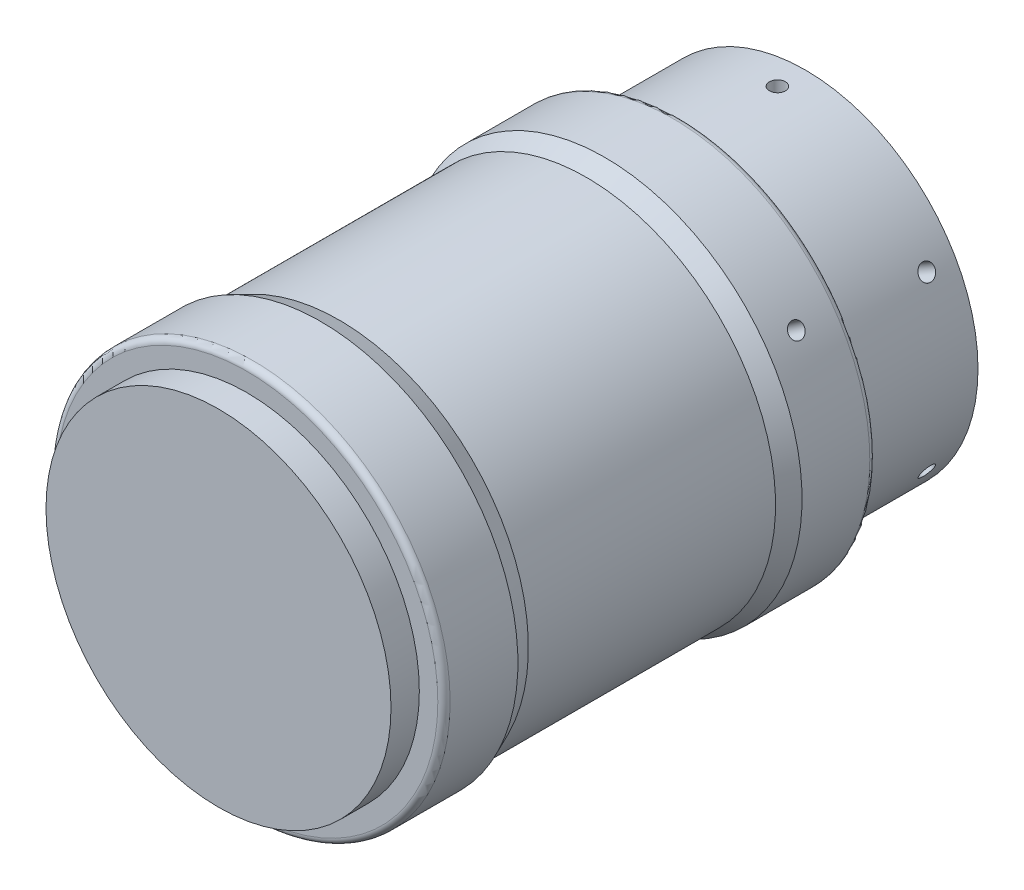
SolidWorks part; units mm, degrees
ref_plane "Front Plane" through (0, 0, 0) normal (0, 0, 1) x (1, 0, 0)
ref_plane "Top Plane" through (0, 0, 0) normal (0, 1, 0) x (1, 0, 0)
ref_plane "Right Plane" through (0, 0, 0) normal (1, 0, 0) x (0, 0, -1)
sketch "Sketch1" plane through (0, 0, 0) normal (0, 0, 1) x (1, 0, 0)
  circle A0 centre (0, 0) radius 28
  dimension "D1" = 56
extrude "Boss-Extrude1" add sketch "Sketch1" along normal blind 20.56
sketch "Sketch2" plane through (0, 0, 20.56) normal (0, 0, 1) x (1, 0, 0)
  circle A0 centre (0, 0) radius 30.7
  dimension "D1" = 61.4
extrude "Boss-Extrude2" add sketch "Sketch2" along normal blind 70.12
sketch "Sketch3" plane through (0, 0, 90.68) normal (0, 0, 1) x (1, 0, 0)
  circle A0 centre (0, 0) radius 28
  dimension "D1" = 56
extrude "Boss-Extrude3" add sketch "Sketch3" along normal blind 4.6
sketch "Sketch4" plane through (0, 0, 0) normal (1, 0, 0) x (0, 0, -1)
  line L0 (-20.56, 30.7) -> (-20.56, 32)
  line L1 (-20.56, 32) -> (-32.56, 32)
  line L2 (-32.56, 32) -> (-35.56, 30.7)
  line L3 (-20.56, 30.7) -> (-90.68, 30.7) construction
  line L4 (-35.56, 30.7) -> (-20.56, 30.7)
  line L5 (-55.62, 30.7) -> (-55.62, 42.3595) construction
  line L6 (-75.68, 30.7) -> (-90.68, 30.7)
  line L7 (-90.68, 30.7) -> (-90.68, 32)
  line L8 (-90.68, 32) -> (-78.68, 32)
  line L9 (-78.68, 32) -> (-75.68, 30.7)
  line L10 (0, 0) -> (-95.1623, 0) construction
  dimension "D1" = 15
  dimension "D2" = 12
  dimension "D3" = 1.3
revolve "Revolve1" add sketch "Sketch4" angle 360 about L10
hole_wizard "#5-40 Tapped Hole1" positions "3DSketch1" profile "Sketch6" tap size "#5-40" standard "ANSI Inch" end condition through all
sketch3d "3DSketch1"
  line L0 (0, 0, 0) -> (0, 28, 0) construction
  line L2 (0, 0, 0) -> (-24.2487, 14, 0) construction
  line L4 (0, 0, 0) -> (1.5469, 1.5469, 0)
  line L5 (24.2487, 14, 0) -> (0, 0, 0) construction
  circle A1 centre (0, 0, 0) radius 28 construction
  point P0 (24.2487, 14, 4.56)
  point P2 (-0.0096, 28, 4.56)
  point P4 (-24.2487, 14, 4.56)
  point P18 (0, 0, 28)
  dimension "D1" = 16
  dimension "D2" = 16
  dimension "D3" = 16
  dimension "D4" = 60
  dimension "D5" = 60
sketch "Sketch6" plane through (24.2487, 14, 4.56) normal (0, 0, 1) x (-0.5, 0.866, 0)
  line L0 (0, 0) -> (0, 71.7128)
  line L1 (0, 71.7128) -> (1.289, 71.7128)
  line L2 (1.289, 71.7128) -> (1.289, 0)
  line L5 (1.289, 0) -> (0, 0)
  line L11 (0, -6.35) -> (0, 107.95) construction
  dimension "Thru Tap Drill Dia." = 2.5781
  dimension "Thru Tap Drill Depth" = 71.7128
cosmetic thread "Hole Thread1" parameters "D2"=3.175
cosmetic thread "Hole Thread2" parameters "D2"=3.175
cosmetic thread "Hole Thread3" parameters "D2"=3.175
hole_wizard "M3x0.5 Tapped Hole1" positions "3DSketch2" profile "Sketch8" tap size "M3x0.5" standard "ANSI Metric"
sketch3d "3DSketch2"
  line L0 (0, 0, 0) -> (0, 28, 0) construction
  line L2 (0, 0, 0) -> (26.2129, 18.3544, 0) construction
  line L4 (0, 0, 0) -> (-26.2129, 18.3544, 0) construction
  circle A0 centre (0, 0, 0) radius 28 construction
  point P0 (26.2129, 18.3544, 27.6963)
  point P2 (-26.2129, 18.3544, 82)
  point P10 (0, 0, 28)
  dimension "D1" = 55
  dimension "D2" = 55
  dimension "D3" = 32
  dimension "D4" = 32
  dimension "D5" = 82
sketch "Sketch8" plane through (26.2129, 18.3544, 27.6963) normal (0, 0, 1) x (-0.5736, 0.8192, 0)
  line L0 (0, 0) -> (0, 8.2511)
  line L1 (0, 8.2511) -> (1.25, 7.5)
  line L2 (1.25, 7.5) -> (1.25, 0)
  line L5 (1.25, 0) -> (0, 0)
  line L10 (0, 8.2511) -> (-1.25, 7.5) construction
  line L11 (0, -6.35) -> (0, 107.95) construction
  dimension "Tap Drill Dia." = 2.5
  dimension "Tap Drill Depth" = 7.5
  dimension "Drill Angle" = 118
cosmetic thread "Hole Thread4" parameters "D1"=6, "D2"=3
cosmetic thread "Hole Thread5" parameters "D1"=6, "D2"=3
fillet "Fillet1" radius 1 2 edges at (-32, 0, 90.68) (-32, 0, 20.56)
